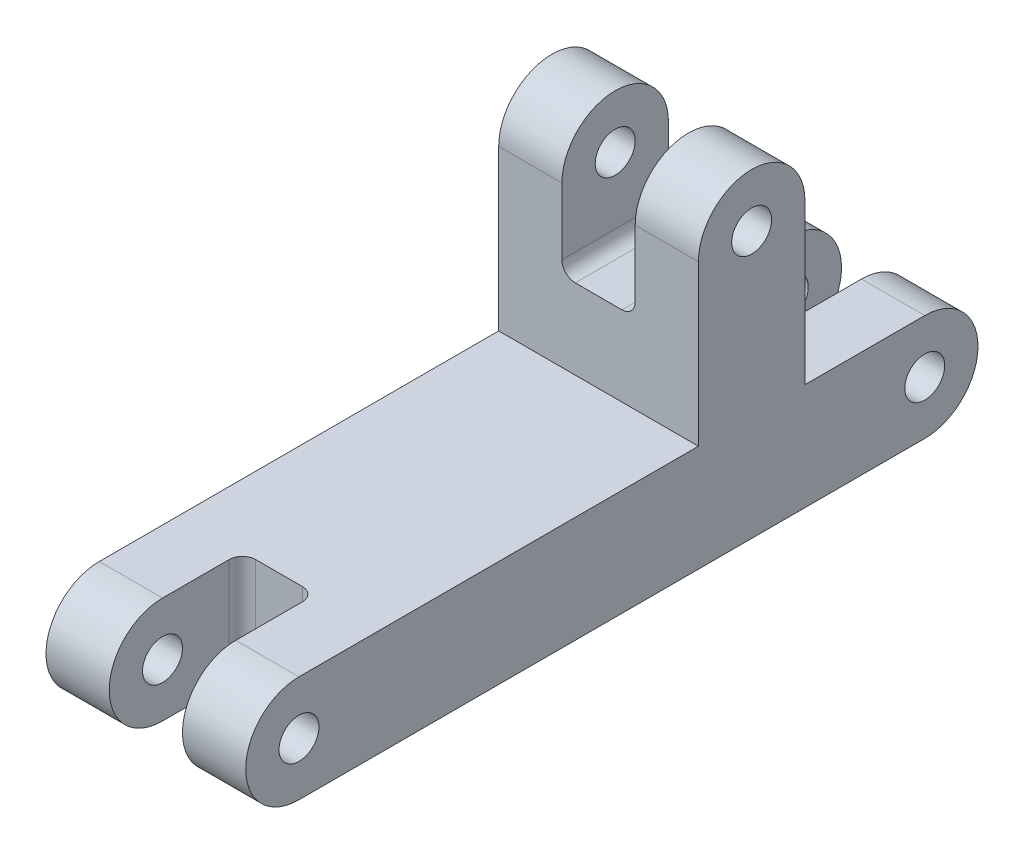
SolidWorks part; units mm, degrees
ref_plane "Alzado" through (0, 0, 0) normal (0, 0, 1) x (1, 0, 0)
ref_plane "Planta" through (0, 0, 0) normal (0, 1, 0) x (1, 0, 0)
ref_plane "Vista lateral" through (0, 0, 0) normal (1, 0, 0) x (0, 0, -1)
sketch "Croquis1" plane through (0, 0, 0) normal (1, 0, 0) x (0, 0, -1)
  line L0 (-4.5, 0) -> (4.5, 0) construction
  line L1 (-4.5, 4) -> (-12.5, 4) construction
  line L2 (-4.5, -4) -> (4.5, -4)
  line L3 (-4.5, 4) -> (4.5, 4)
  line L5 (-12.5, 4) -> (-12.5, 16)
  line L6 (-12.5, 16) -> (-4.5, 16) construction
  line L7 (-4.5, 4) -> (-4.5, 16)
  line L8 (-12.5, 4) -> (-42.5, 4)
  line L9 (-4.5, -4) -> (-42.5, -4)
  line L10 (-42.5, 4) -> (-42.5, -4) construction
  arc A0 (-4.5, 4) -> (-4.5, -4) centre (-4.5, 0) ccw construction
  arc A1 (4.5, -4) -> (4.5, 4) centre (4.5, 0) ccw
  circle A2 centre (4.5, 0) radius 1.5
  arc A3 (-4.5, 16) -> (-12.5, 16) centre (-8.5, 16) ccw
  circle A4 centre (-8.5, 16) radius 1.5
  circle A5 centre (-4.5, 0) radius 1.5 construction
  arc A6 (-42.5, 4) -> (-42.5, -4) centre (-42.5, 0) ccw
  circle A7 centre (-42.5, 0) radius 1.5
  point P3 (0, 0)
  dimension "D2" = 4
  dimension "D3" = 3
  dimension "D4" = 4
  dimension "D7" = 30
  dimension "D1" = 9
  dimension "D6" = 12
extrude "Saliente-Extruir1" add sketch "Croquis1" along normal mid plane 15
sketch "Croquis2" plane through (0, 0, 0) normal (1, 0, 0) x (0, 0, -1)
  line L0 (-12.5, 16) -> (-12.5, 4) construction
  line L1 (-12.5, 10) -> (-4.5, 10)
  line L2 (-12.5, 10) -> (-12.5, 20)
  line L3 (-12.5, 20) -> (-4.5, 20)
  line L4 (-4.5, 10) -> (-4.5, 20)
  line L5 (-4.5, 4) -> (-4.5, 16) construction
  line L11 (-42.5, -4) -> (4.5, -4) construction
  line L12 (4.5, 4) -> (-4.5, 4) construction
  line L13 (-7.5, 4) -> (8.5, 4)
  line L14 (-7.5, 4) -> (-7.5, -4)
  line L15 (-7.5, -4) -> (8.5, -4)
  line L16 (8.5, 4) -> (8.5, -4)
  line L18 (-36.5, 4) -> (-46.5, 4)
  line L19 (-36.5, 4) -> (-36.5, -4)
  line L20 (-36.5, -4) -> (-46.5, -4)
  line L21 (-46.5, 4) -> (-46.5, -4)
  line L22 (-42.5, -4) -> (4.5, -4) construction
  line L23 (-12.5, 4) -> (-42.5, 4) construction
  arc A0 (-4.5, 16) -> (-12.5, 16) centre (-8.5, 16) ccw construction
  arc A2 (4.5, -4) -> (4.5, 4) centre (4.5, 0) ccw construction
  arc A5 (-42.5, 4) -> (-42.5, -4) centre (-42.5, 0) ccw construction
  dimension "D5" = 10
  dimension "D1" = 10
  dimension "D3" = 16
extrude "Cortar-Extruir1" cut sketch "Croquis2" against normal mid plane 5.5
fillet "Redondeo1" radius 1 6 edges at (2.75, 0, 36.5) (-2.75, 0, 36.5) (2.75, 0, 7.5) (-2.75, 0, 7.5) (2.75, 10, 8.5) (-2.75, 10, 8.5)
